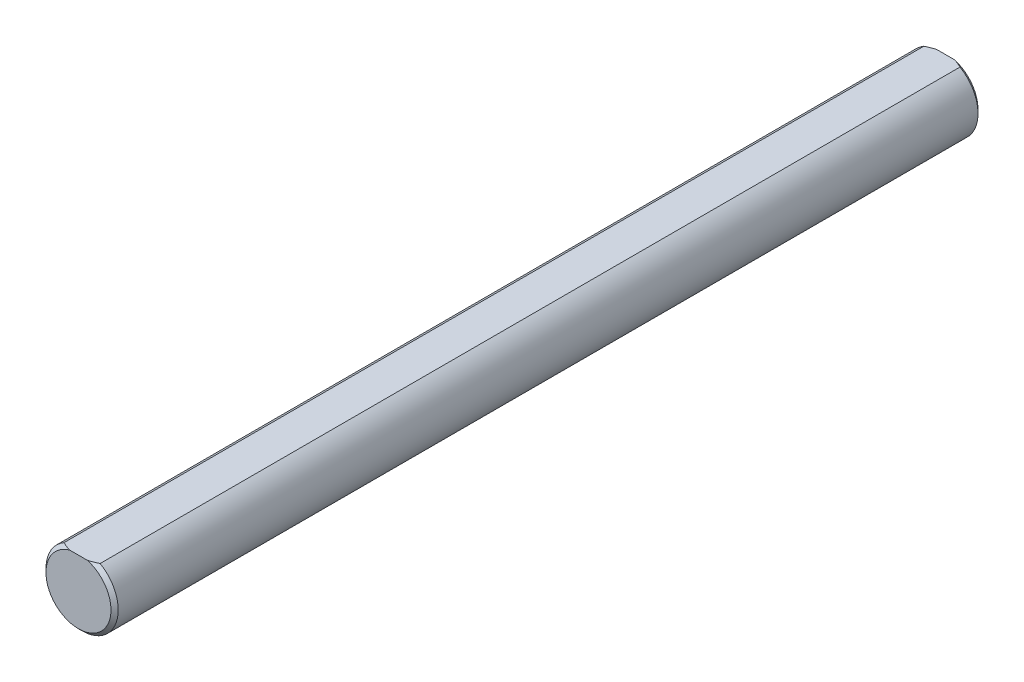
SolidWorks part; units mm, degrees
ref_plane "Front Plane" through (0, 0, 0) normal (0, 0, 1) x (1, 0, 0)
ref_plane "Top Plane" through (0, 0, 0) normal (0, 1, 0) x (1, 0, 0)
ref_plane "Right Plane" through (0, 0, 0) normal (1, 0, 0) x (0, 0, -1)
sketch "Sketch1" plane through (0, 0, 0) normal (0, 0, 1) x (1, 0, 0)
  line L0 (-3.175, 5.4993) -> (3.175, 5.4993) construction
  circle A1 centre (0, 0) radius 6.35 construction
  dimension "Diameter" = 12.7
  dimension "Flat Width" = 6.35
sketch "Sketch2" plane through (0, 0, 0) normal (1, 0, 0) x (0, 0, -1)
  line L0 (-76.2, 6.35) -> (76.2, 6.35) construction
  line L1 (0, 6.35) -> (0, -6.35) construction
  line L2 (0, 6.35) -> (0, -6.35) construction
  line L3 (-76.2, 6.35) -> (-76.2, -6.35) construction
  line L4 (-76.2, -6.35) -> (76.2, -6.35) construction
  point P2 (0, 6.35)
  point P3 (50.8, 6.35)
  point P4 (-50.8, 6.35)
  dimension "Length" = 152.4
  dimension "D2" = 25.4
  dimension "D1" = 25.4
  dimension "D-Profile Length" = 152.4
sketch "Sketch3" plane through (0, 0, 0) normal (0, 0, 1) x (1, 0, 0)
  circle A1 centre (0, 0) radius 6.35 construction
  circle A3 centre (0, 0) radius 6.35
extrude "Boss-Extrude2" add sketch "Sketch3" along normal up to vertex (76.2 mm away) and the other way up to vertex (76.2 mm away) up to point (0, 6.35, 76.2) other way up to point (0, 6.35, -76.2)
sketch "Sketch10" plane through (0, 0, 0) normal (0, 0, 1) x (1, 0, 0)
  line L0 (-3.175, 5.4993) -> (3.175, 5.4993)
  line L1 (0, 0) -> (0, 6.35) construction
  circle A0 centre (0, 0) radius 6.35 construction
  circle A1 centre (0, 0) radius 6.35 construction
  arc A2 (-3.175, 5.4993) -> (3.175, 5.4993) centre (0, 0) cw
extrude "Cut-Extrude5" cut sketch "Sketch10" against normal through all both and the other way through all
chamfer "Chamfer1" distance 0.635 angle 45 4 edges at (0, -6.35, 76.2) (0, -6.35, -76.2) (0, 5.4993, -76.2) (0, 5.4993, 76.2)
equation "\"D1@Chamfer1\"= \"Diameter@Sketch1\" / 20"
equation "\"D1@Sketch2\"=\"Diameter@Sketch1\"*2"
equation "\"D2@Sketch2\"=\"D1@Sketch2\""
